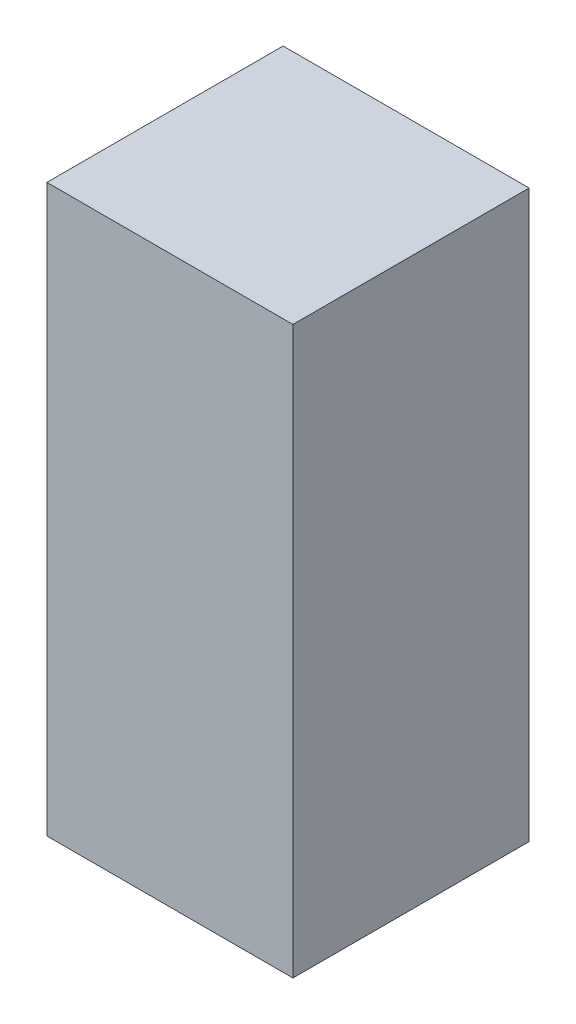
SolidWorks part; units mm, degrees
ref_plane "Front Plane" through (0, 0, 0) normal (0, 0, 1) x (1, 0, 0)
ref_plane "Top Plane" through (0, 0, 0) normal (0, 1, 0) x (1, 0, 0)
ref_plane "Right Plane" through (0, 0, 0) normal (1, 0, 0) x (0, 0, -1)
sketch "Sketch1" plane through (0, 0, 0) normal (0, 0, 1) x (1, 0, 0)
  line L0 (0, 57.5) -> (0, -57.5) construction
  line L2 (-24.9936, 57.5) -> (24.9936, 57.5)
  line L3 (-24.9936, 57.5) -> (-24.9936, -57.5)
  line L4 (-24.9936, -57.5) -> (24.9936, -57.5)
  line L5 (24.9936, 57.5) -> (24.9936, -57.5)
  line L6 (-24.9936, 57.5) -> (24.9936, -57.5) construction
  line L7 (-24.9936, -57.5) -> (24.9936, 57.5) construction
  point P3 (0, 0)
  dimension "D1" = 115
extrude "Boss-Extrude1" add sketch "Sketch1" along normal blind 48
